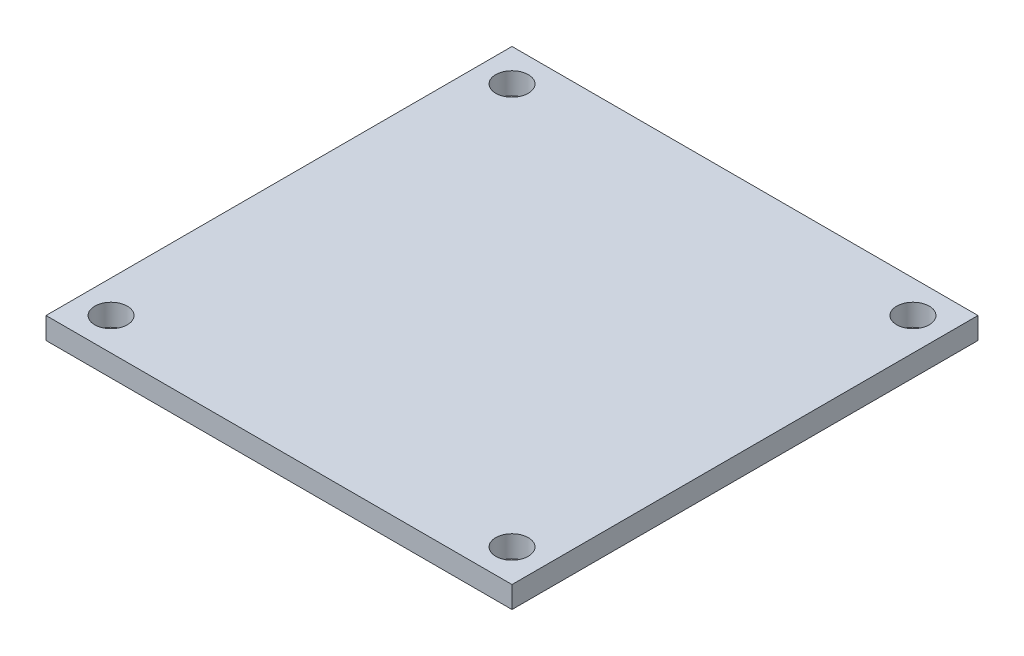
SolidWorks part; units mm, degrees
ref_plane "前视基准面" through (0, 0, 0) normal (0, 0, 1) x (1, 0, 0)
ref_plane "上视基准面" through (0, 0, 0) normal (0, 1, 0) x (1, 0, 0)
ref_plane "右视基准面" through (0, 0, 0) normal (1, 0, 0) x (0, 0, -1)
sketch "草图2" plane through (0, 0, 0) normal (0, 1, 0) x (1, 0, 0)
  line L1 (-21.5, 21.5) -> (21.5, 21.5)
  line L2 (-21.5, 21.5) -> (-21.5, -21.5)
  line L3 (-21.5, -21.5) -> (21.5, -21.5)
  line L4 (21.5, 21.5) -> (21.5, -21.5)
  line L5 (-21.5, 21.5) -> (21.5, -21.5) construction
  line L6 (-21.5, -21.5) -> (21.5, 21.5) construction
  line L11 (-18.5, 18.5) -> (18.5, -18.5) construction
  line L12 (-18.5, -18.5) -> (18.5, 18.5) construction
  circle A0 centre (-18.5, 18.5) radius 1.5
  circle A1 centre (-18.5, -18.5) radius 1.5
  circle A2 centre (18.5, 18.5) radius 1.5
  circle A3 centre (18.5, -18.5) radius 1.5
  point P0 (0, 0)
  point P6 (0, 0)
  dimension "D4" = 3
  dimension "D1" = 43
  dimension "D2" = 43
  dimension "D3" = 37
extrude "凸台-拉伸1" add sketch "草图2" along normal blind 2
